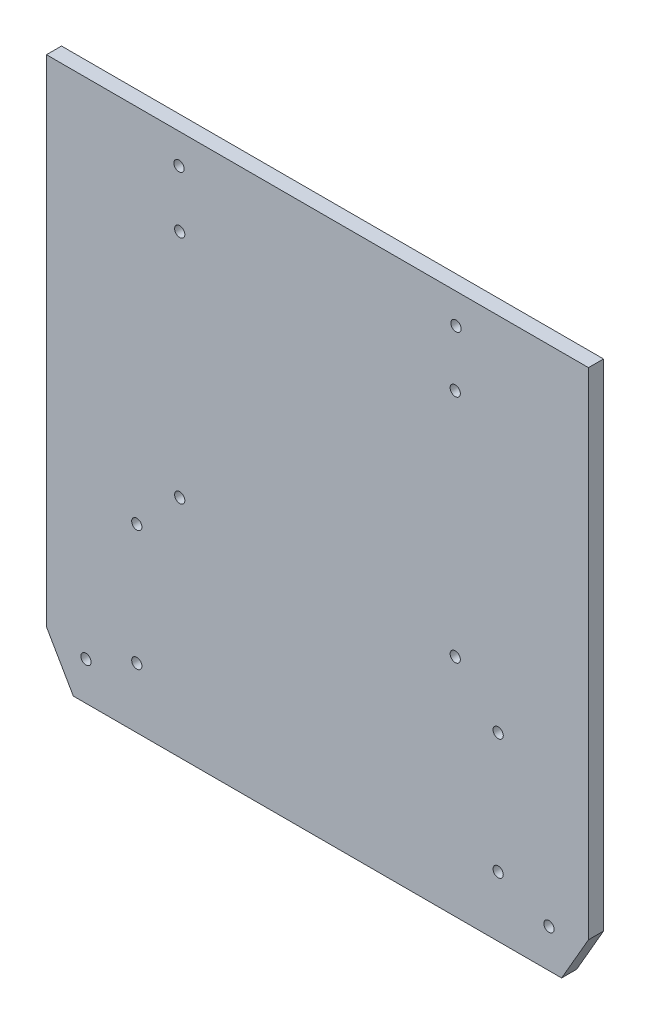
SolidWorks part; units mm, degrees
ref_plane "前基準面" through (0, 0, 0) normal (0, 0, 1) x (1, 0, 0)
ref_plane "上基準面" through (0, 0, 0) normal (0, 1, 0) x (1, 0, 0)
ref_plane "右基準面" through (0, 0, 0) normal (1, 0, 0) x (0, 0, -1)
sketch "草圖1" plane through (0, 0, 0) normal (0, 0, 1) x (1, 0, 0)
  line L1 (-90, 90) -> (90, 90)
  line L2 (-90, 90) -> (-90, -90)
  line L3 (-90, -90) -> (90, -90)
  line L4 (90, 90) -> (90, -90)
  point P4 (0, 90)
  point P6 (90, 0)
  dimension "D1" = 180
  dimension "D2" = 180
extrude "填料-伸長1" add sketch "草圖1" along normal blind 5
sketch "草圖2" plane through (0, 0, 5) normal (0, 0, 1) x (1, 0, 0)
  line L0 (0, 90) -> (0, -90) construction
  line L1 (90, 90) -> (-90, 90) construction
  line L2 (-90, -90) -> (90, -90) construction
  circle A0 centre (-46, 80) radius 1.7
  circle A1 centre (46, 80) radius 1.7
  dimension "D2" = 3.4
  dimension "D1" = 10
  dimension "D3" = 46
extrude "除料-伸長1" cut sketch "草圖2" against normal through all
sketch "草圖3" plane through (0, 0, 5) normal (0, 0, 1) x (1, 0, 0)
  line L0 (-185, 90) -> (185, 90) construction
  line L2 (90, 90) -> (-90, 90) construction
  line L3 (-185, 90) -> (0, -230.4294) construction
  line L4 (0, -230.4294) -> (185, 90) construction
  line L5 (-90, -90) -> (-81.077, -90)
  line L6 (-90, -90) -> (90, -90) construction
  line L7 (-81.077, -90) -> (-90, -74.5448)
  line L8 (-90, 90) -> (-90, -90) construction
  line L9 (-90, -74.5448) -> (-90, -90)
  line L10 (90, -90) -> (81.077, -90)
  line L11 (81.077, -90) -> (90, -74.5448)
  line L12 (90, -90) -> (90, 90) construction
  line L13 (90, -74.5448) -> (90, -90)
  point P5 (0, 90)
  dimension "D1" = 370
  dimension "D2" = 370
  dimension "D3" = 370
extrude "除料-伸長2" cut sketch "草圖3" against normal through all
sketch "草圖4" plane through (0, 0, 5) normal (0, 0, 1) x (1, 0, 0)
  line L0 (0, 90) -> (0, -90) construction
  line L1 (90, 90) -> (-90, 90) construction
  line L2 (-81.077, -90) -> (81.077, -90) construction
  line L3 (-81.077, -90) -> (-90, -74.5448) construction
  line L4 (-85.5385, -82.2724) -> (-76.8782, -77.2724) construction
  line L5 (85.5385, -82.2724) -> (76.8782, -77.2724) construction
  circle A0 centre (-76.8782, -77.2724) radius 1.7
  circle A1 centre (76.8782, -77.2724) radius 1.7
  dimension "D2" = 3.4
  dimension "D1" = 10
  dimension "D3" = 10
extrude "除料-伸長3" cut sketch "草圖4" against normal through all
sketch "草圖5" plane through (0, 0, 5) normal (0, 0, 1) x (1, 0, 0)
  line L1 (-49.5, 65) -> (49.5, 65) construction
  line L2 (-49.5, 65) -> (-49.5, -19) construction
  line L3 (-49.5, -19) -> (49.5, -19) construction
  line L4 (49.5, 65) -> (49.5, -19) construction
  line L5 (0, 65) -> (0, -19) construction
  line L6 (49.5, 23) -> (-49.5, 23) construction
  line L7 (90, 90) -> (-90, 90) construction
  circle A0 centre (-45.75, 61.25) radius 1.7
  circle A1 centre (45.75, 61.25) radius 1.7
  circle A2 centre (45.75, -15.25) radius 1.7
  circle A3 centre (-45.75, -15.25) radius 1.7
  point P4 (0, 65)
  dimension "D6" = 3.4
  dimension "D1" = 99
  dimension "D2" = 84
  dimension "D3" = 25
  dimension "D4" = 3.75
  dimension "D5" = 3.75
extrude "除料-伸長4" cut sketch "草圖5" against normal through all
sketch "草圖6" plane through (0, 0, 5) normal (0, 0, 1) x (1, 0, 0)
  line L0 (0, 90) -> (0, -90) construction
  line L1 (90, 90) -> (-90, 90) construction
  line L2 (-81.077, -90) -> (81.077, -90) construction
  line L3 (50, -40) -> (50, -60) construction
  line L4 (-70, -40) -> (-50, -40) construction
  line L5 (-70, -40) -> (-70, -60) construction
  line L6 (-70, -60) -> (-50, -60) construction
  line L7 (-50, -40) -> (-50, -60) construction
  line L8 (70, -60) -> (50, -60) construction
  line L9 (70, -40) -> (70, -60) construction
  line L10 (70, -40) -> (50, -40) construction
  circle A0 centre (-60, -30) radius 1.7
  circle A1 centre (-60, -70) radius 1.7
  circle A2 centre (60, -70) radius 1.7
  circle A3 centre (60, -30) radius 1.7
  point P10 (-60, -40)
  dimension "D1" = 120
  dimension "D2" = 3.4
  dimension "D4" = 3.4
  dimension "D3" = 60
  dimension "D5" = 40
  dimension "D6" = 20
  dimension "D7" = 20
  dimension "D8" = 10
  dimension "D9" = 10
extrude "除料-伸長5" cut sketch "草圖6" against normal through all
